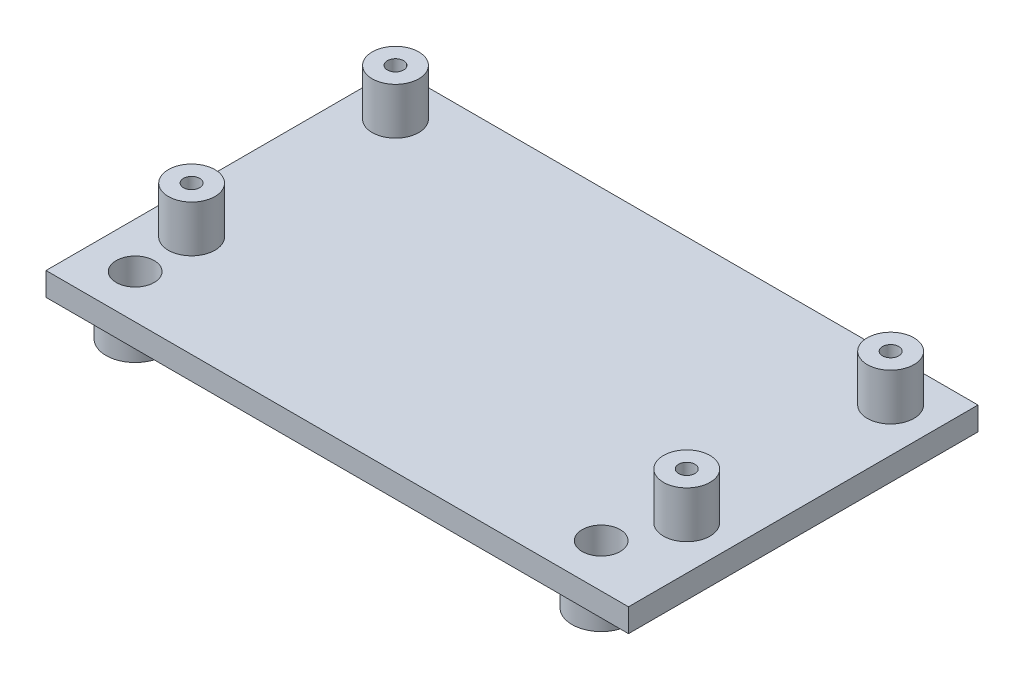
SolidWorks part; units mm, degrees
ref_plane "Front Plane" through (0, 0, 0) normal (0, 0, 1) x (1, 0, 0)
ref_plane "Top Plane" through (0, 0, 0) normal (0, 1, 0) x (1, 0, 0)
ref_plane "Right Plane" through (0, 0, 0) normal (1, 0, 0) x (0, 0, -1)
sketch "Sketch1" plane through (0, 0, 0) normal (0, 1, 0) x (1, 0, 0)
  line L1 (0, 0) -> (50, 0) construction
  line L2 (0, 0) -> (0, 30) construction
  line L3 (0, 30) -> (50, 30) construction
  line L4 (50, 0) -> (50, 30) construction
  line L5 (0, 30) -> (50, 30) construction
  line L6 (0, 30) -> (0, 15) construction
  line L7 (0, 15) -> (50, 15) construction
  line L8 (50, 30) -> (50, 15) construction
  line L9 (2.5, 7.5) -> (47.5, 7.5) construction
  line L10 (2.5, 7.5) -> (2.5, 27.5) construction
  line L11 (2.5, 27.5) -> (47.5, 27.5) construction
  line L12 (47.5, 7.5) -> (47.5, 27.5) construction
  line L13 (3.75, 8.75) -> (46.25, 8.75) construction
  line L14 (3.75, 8.75) -> (3.75, 26.25) construction
  line L15 (3.75, 26.25) -> (46.25, 26.25) construction
  line L16 (46.25, 8.75) -> (46.25, 26.25) construction
  circle A0 centre (3.75, 26.25) radius 2
  circle A1 centre (46.25, 26.25) radius 2
  circle A2 centre (46.25, 8.75) radius 2
  circle A3 centre (3.75, 8.75) radius 2
  dimension "D6" = 4
  dimension "D7" = 4
  dimension "D8" = 4
  dimension "D9" = 4
  dimension "D1" = 50
  dimension "D2" = 30
  dimension "D3" = 15
  dimension "D4" = 42.5
  dimension "D5" = 17.5
  dimension "D10" = 1.25
  dimension "D11" = 1.25
  dimension "D12" = 20
  dimension "D13" = 45
  dimension "D14" = 2.5
  dimension "D15" = 2.5
extrude "Boss-Extrude1" add sketch "Sketch1" along normal blind 4
sketch "Sketch2" plane through (0, 0, 0) normal (0, 1, 0) x (1, 0, 0)
  line L0 (0, 30) -> (50, 30)
  line L1 (50, 30) -> (50, 0)
  line L2 (0, 30) -> (0, 0)
  line L3 (0, 0) -> (50, 0)
extrude "Boss-Extrude2" add sketch "Sketch2" against normal blind 2
hole_wizard "#00 Clearance Hole2" positions "Sketch8" profile "Sketch7" hole size "#00" standard "ANSI Inch" end condition through all
sketch "Sketch8" plane through (0, 4, 0) normal (0, 1, 0) x (1, 0, 0)
  point P0 (3.75, 26.25)
  point P3 (46.25, 26.25)
  point P6 (46.25, 8.75)
  point P9 (3.75, 8.75)
sketch "Sketch7" plane through (3.75, 4, -26.25) normal (1, 0, 0) x (0, 0, 1)
  line L0 (0, 0) -> (0, 6)
  line L1 (0, 6) -> (0.6985, 6)
  line L2 (0.6985, 6) -> (0.6985, 0)
  line L5 (0.6985, 0) -> (0, 0)
  line L11 (0, -6.35) -> (0, 107.95) construction
  dimension "Thru Hole Dia." = 1.397
  dimension "Thru Hole Depth" = 6
sketch "Sketch9" plane through (0, -2, 0) normal (0, -1, 0) x (1, 0, 0)
  line L0 (3.75, -8.75) -> (46.25, -8.75) construction
  circle A0 centre (3.9059, -3.75) radius 2.5
  circle A1 centre (43.9059, -3.75) radius 2.5
  dimension "D1" = 5
  dimension "D2" = 5
  dimension "D3" = 40
  dimension "D4" = 5
extrude "Boss-Extrude3" add sketch "Sketch9" along normal blind 3
hole_wizard "#4 Clearance Hole1" positions "Sketch11" profile "Sketch10" hole size "#4" standard "ANSI Inch" end condition through all
sketch "Sketch11" plane through (0, -5, 0) normal (0, -1, 0) x (-1, 0, 0)
  point P0 (-3.9059, 3.75)
  point P3 (-43.9059, 3.75)
sketch "Sketch10" plane through (3.9059, -5, -3.75) normal (1, 0, 0) x (0, 0, -1)
  line L0 (0, 0) -> (0, 9)
  line L1 (0, 9) -> (1.6319, 9)
  line L2 (1.6319, 9) -> (1.6319, 0)
  line L5 (1.6319, 0) -> (0, 0)
  line L11 (0, -6.35) -> (0, 107.95) construction
  dimension "Thru Hole Dia." = 3.2639
  dimension "Thru Hole Depth" = 9
